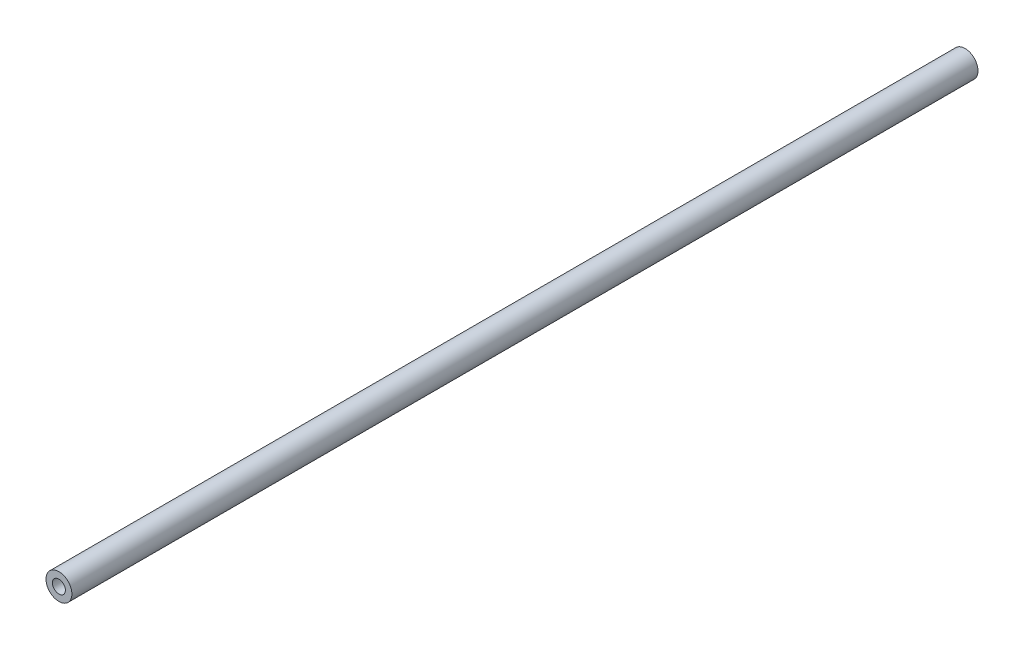
SolidWorks part; units mm, degrees
ref_plane "前视基准面" through (0, 0, 0) normal (0, 0, 1) x (1, 0, 0)
ref_plane "上视基准面" through (0, 0, 0) normal (0, 1, 0) x (1, 0, 0)
ref_plane "右视基准面" through (0, 0, 0) normal (1, 0, 0) x (0, 0, -1)
other "Configuration Table"
sketch "草图1" plane through (0, 0, 0) normal (0, 0, 1) x (1, 0, 0)
  circle A0 centre (0, 0) radius 4
  dimension "D1" = 8
extrude "凸台-拉伸1" add sketch "草图1" along normal blind 280
sketch "草图2" plane through (0, 0, 280) normal (0, 0, 1) x (1, 0, 0)
  circle A0 centre (0, 0) radius 2
  dimension "D1" = 4
extrude "切除-拉伸1" cut sketch "草图2" against normal blind 10
sketch "草图3" plane through (0, 0, 0) normal (0, 0, -1) x (-1, 0, 0)
  circle A0 centre (0, 0) radius 2
  dimension "D1" = 4
extrude "切除-拉伸2" cut sketch "草图3" against normal blind 10
